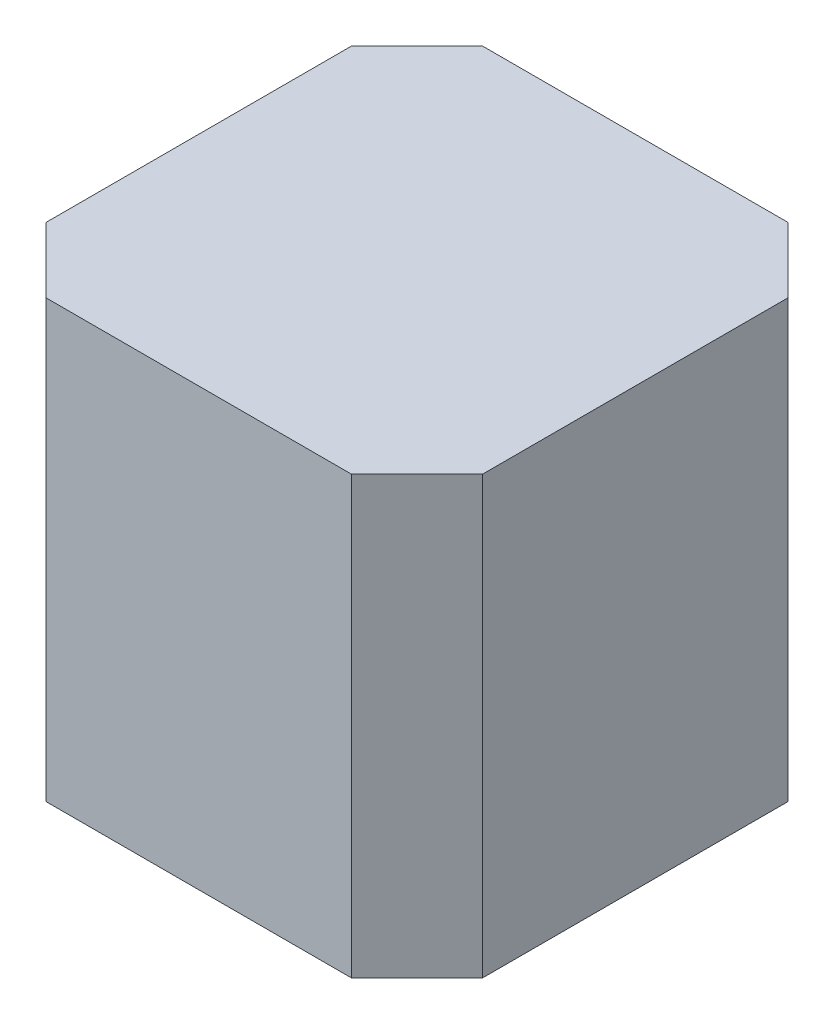
SolidWorks part; units mm, degrees
ref_plane "Front Plane" through (0, 0, 0) normal (0, 0, 1) x (1, 0, 0)
ref_plane "Top Plane" through (0, 0, 0) normal (0, 1, 0) x (1, 0, 0)
ref_plane "Right Plane" through (0, 0, 0) normal (1, 0, 0) x (0, 0, -1)
sketch "Sketch1" plane through (0, 0, 0) normal (0, 1, 0) x (1, 0, 0)
  line L0 (-1.27, 1.27) -> (1.27, -1.27) construction
  line L1 (-1.27, 1.27) -> (1.27, 1.27)
  line L2 (-1.27, 1.27) -> (-1.27, -1.27)
  line L3 (-1.27, -1.27) -> (1.27, -1.27)
  line L4 (1.27, 1.27) -> (1.27, -1.27)
  point P4 (0, 0)
  dimension "D1" = 2.54
  dimension "D2" = 2.54
extrude "Boss-Extrude1" add sketch "Sketch1" along normal blind 2.54
chamfer "Chamfer1" distance 0.381 angle 45 4 edges at (-1.27, 1.27, -1.27) (1.27, 1.27, -1.27) (1.27, 1.27, 1.27) (-1.27, 1.27, 1.27)
